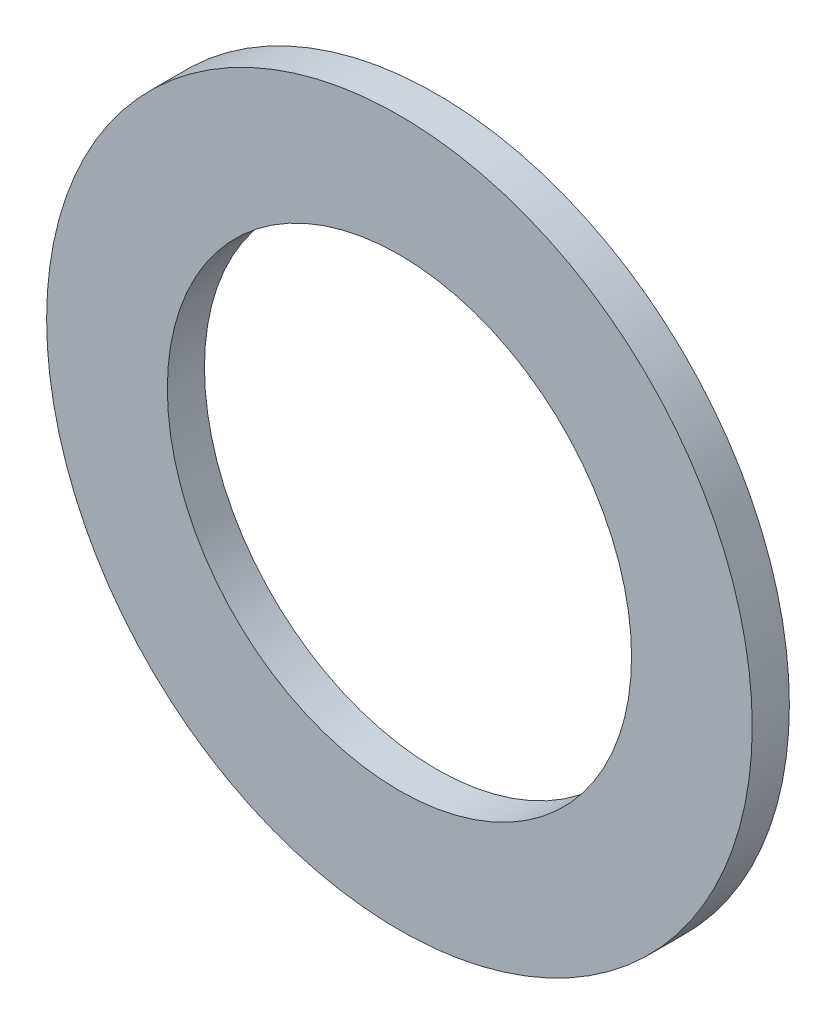
SolidWorks part; units mm, degrees
ref_plane "Front Plane" through (0, 0, 0) normal (0, 0, 1) x (1, 0, 0)
ref_plane "Top Plane" through (0, 0, 0) normal (0, 1, 0) x (1, 0, 0)
ref_plane "Right Plane" through (0, 0, 0) normal (1, 0, 0) x (0, 0, -1)
sketch "Sketch1" plane through (0, 0, 0) normal (0, 0, 1) x (1, 0, 0)
  circle A0 centre (0, 0) radius 3.175
  circle A1 centre (0, 0) radius 4.826
  dimension "ID" = 6.35
  dimension "OD" = 9.652
extrude "Extrude1" add sketch "Sketch1" against normal blind 0.508
